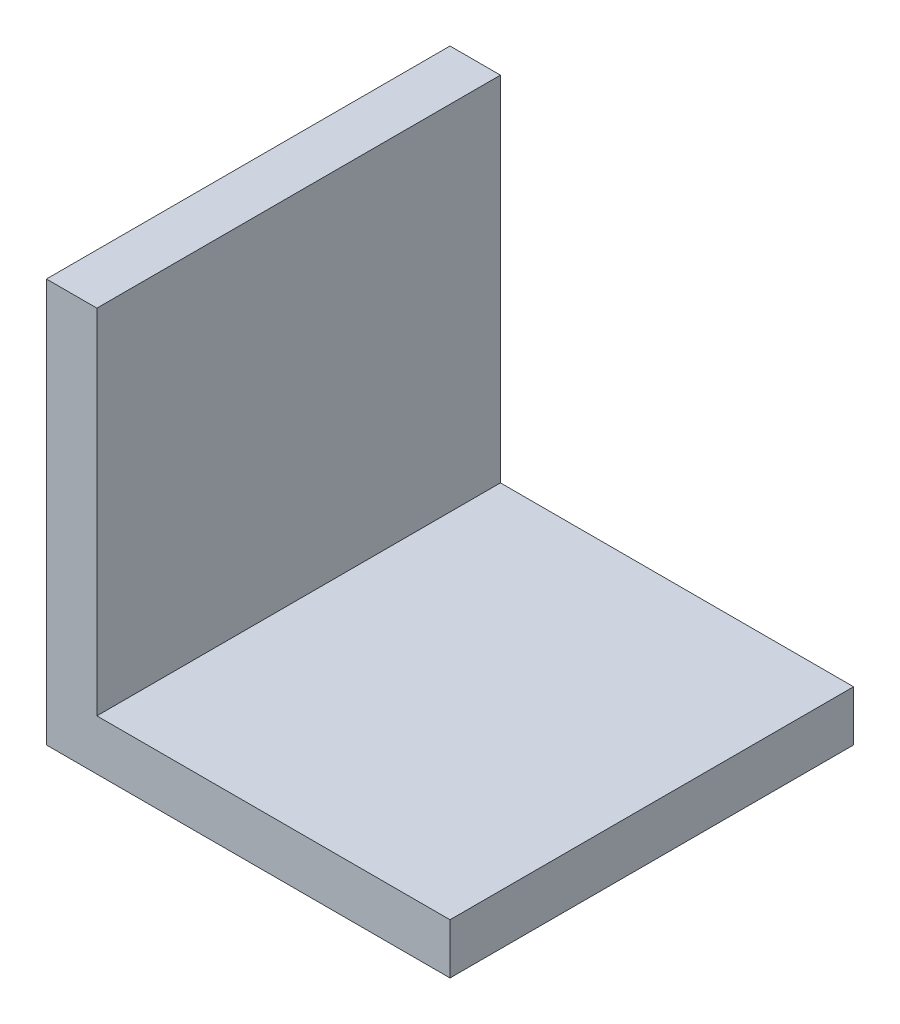
SolidWorks part; units mm, degrees
material "6061 Alloy"
ref_plane "Front Plane" through (0, 0, 0) normal (0, 0, 1) x (1, 0, 0)
ref_plane "Top Plane" through (0, 0, 0) normal (0, 1, 0) x (1, 0, 0)
ref_plane "Right Plane" through (0, 0, 0) normal (1, 0, 0) x (0, 0, -1)
sketch "Sketch1" plane through (0, 0, 0) normal (0, 0, 1) x (1, 0, 0)
  line L0 (0, 0) -> (0, 25.4)
  line L1 (0, 0) -> (25.4, 0)
  line L2 (3.175, 3.175) -> (25.4, 3.175)
  line L3 (3.175, 3.175) -> (3.175, 25.4)
  line L4 (3.175, 25.4) -> (0, 25.4)
  line L5 (25.4, 3.175) -> (25.4, 0)
  dimension "D1" = 25.4
  dimension "D2" = 25.4
  dimension "D3" = 3.175
extrude "Boss-Extrude1" add sketch "Sketch1" along normal blind 25.4
